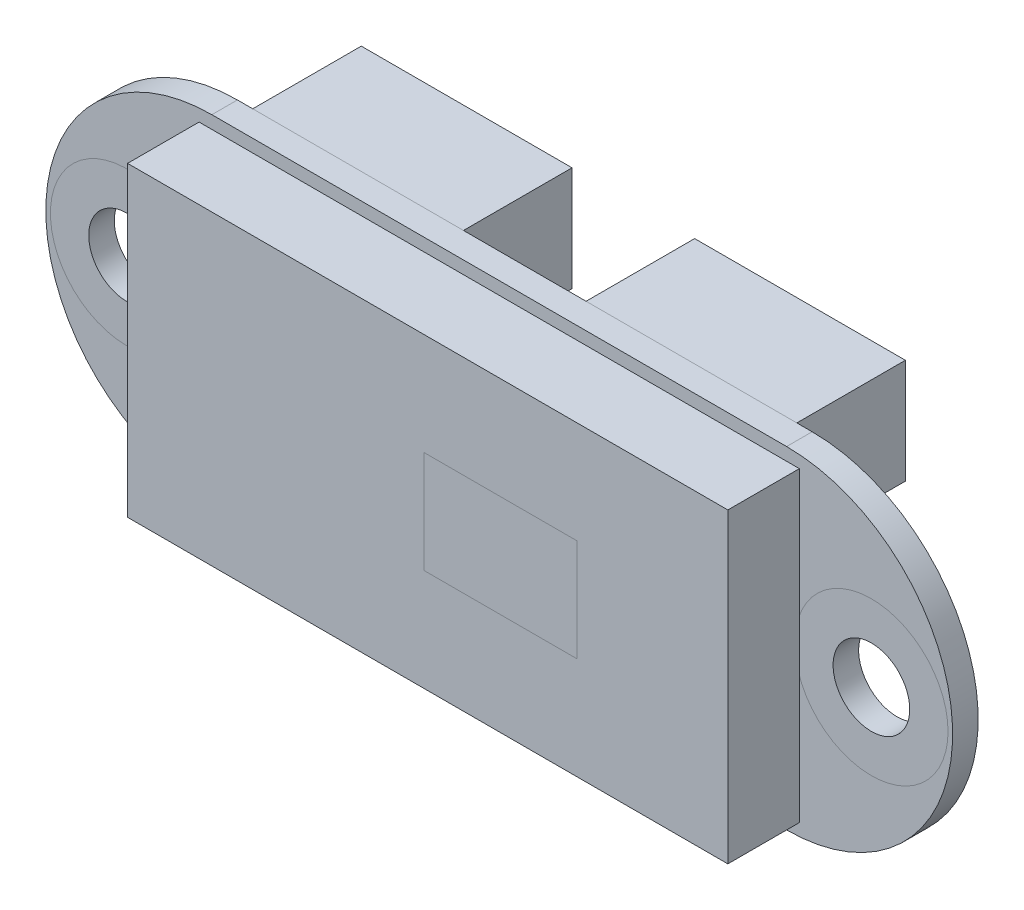
SolidWorks part; units mm, degrees
ref_plane "前视基准面" through (0, 0, 0) normal (0, 0, 1) x (1, 0, 0)
ref_plane "上视基准面" through (0, 0, 0) normal (0, 1, 0) x (1, 0, 0)
ref_plane "右视基准面" through (0, 0, 0) normal (1, 0, 0) x (0, 0, -1)
sketch "草图1" plane through (0, 0, 0) normal (0, 0, 1) x (1, 0, 0)
  line L1 (-49.5108, 21.8667) -> (-27.0108, 21.8667)
  line L3 (-49.5108, 8.8667) -> (-27.0108, 8.8667)
  arc A0 (-49.5108, 21.8667) -> (-49.5108, 8.8667) centre (-49.5108, 15.3667) ccw
  arc A1 (-27.0108, 8.8667) -> (-27.0108, 21.8667) centre (-27.0108, 15.3667) ccw
  circle A2 centre (-52.8308, 15.3667) radius 3
  circle A3 centre (-23.6908, 15.3667) radius 3
  point P10 (-38.2608, 21.8667)
  point P11 (-38.2608, 8.8667)
  dimension "D3" = 14.57
  dimension "D5" = 6
  dimension "D6" = 6
  dimension "D1" = 22.5
  dimension "D2" = 13
  dimension "D4" = 14.57
extrude "凸台-拉伸1" add sketch "草图1" along normal blind 1
sketch "草图2" plane through (0, 0, 1) normal (0, 0, 1) x (1, 0, 0)
  circle A0 centre (-52.8308, 15.3667) radius 1.5
  circle A1 centre (-23.6908, 15.3667) radius 1.5
  circle A2 centre (-23.6908, 15.3667) radius 3
  circle A3 centre (-52.8308, 15.3667) radius 3
extrude "凸台-拉伸2" add sketch "草图2" against normal blind 1 separate body
sketch "草图3" plane through (0, 0, 1) normal (0, 0, 1) x (1, 0, 0)
  line L0 (-27.0108, 21.8667) -> (-49.5108, 21.8667) construction
  line L1 (-50.0108, 21.3667) -> (-26.5108, 21.3667)
  line L2 (-50.0108, 21.3667) -> (-50.0108, 9.3667)
  line L3 (-50.0108, 9.3667) -> (-26.5108, 9.3667)
  line L4 (-26.5108, 21.3667) -> (-26.5108, 9.3667)
  line L6 (-38.4108, 17.3667) -> (-32.4108, 17.3667)
  line L7 (-38.4108, 17.3667) -> (-38.4108, 13.3667)
  line L8 (-38.4108, 13.3667) -> (-32.4108, 13.3667)
  line L9 (-32.4108, 17.3667) -> (-32.4108, 13.3667)
  point P4 (-50.0108, 15.3667)
  point P7 (-38.2608, 21.3667)
  point P8 (-38.2608, 21.8667)
  dimension "D1" = 6.5
  dimension "D2" = 12
  dimension "D3" = 23.5
  dimension "D4" = 0
  dimension "D5" = 4
  dimension "D6" = 6
  dimension "D7" = 5.9
  dimension "D8" = 4
extrude "凸台-拉伸3" add sketch "草图3" along normal blind 2.8 separate body
sketch "草图4" plane through (0, 0, 3.8) normal (0, 0, 1) x (1, 0, 0)
  line L1 (-38.4108, 17.3667) -> (-32.4108, 17.3667)
  line L2 (-38.4108, 17.3667) -> (-38.4108, 13.3667)
  line L3 (-38.4108, 13.3667) -> (-32.4108, 13.3667)
  line L4 (-32.4108, 17.3667) -> (-32.4108, 13.3667)
extrude "凸台-拉伸4" add sketch "草图4" against normal blind 2.8 separate body
sketch "草图5" plane through (0, 0, 0) normal (0, 0, -1) x (-1, 0, 0)
  line L0 (27.0108, 21.8667) -> (49.5108, 21.8667) construction
  line L1 (27.6108, 21.8667) -> (35.8608, 21.8667)
  line L2 (27.6108, 21.8667) -> (27.6108, 17.7667)
  line L3 (27.6108, 17.7667) -> (35.8608, 17.7667)
  line L4 (35.8608, 21.8667) -> (35.8608, 17.7667)
  line L5 (49.5108, 8.8667) -> (27.0108, 8.8667) construction
  line L6 (40.6608, 21.8667) -> (48.9108, 21.8667)
  line L7 (40.6608, 21.8667) -> (40.6608, 17.7667)
  line L8 (40.6608, 17.7667) -> (48.9108, 17.7667)
  line L9 (48.9108, 21.8667) -> (48.9108, 17.7667)
  point P10 (31.7358, 21.8667)
  point P11 (38.2608, 21.8667)
  point P12 (44.7858, 21.8667)
  point P15 (38.2608, 8.8667)
  dimension "D1" = 8.25
  dimension "D2" = 4.1
  dimension "D3" = 4.1
  dimension "D4" = 8.25
  dimension "D5" = 6.525
  dimension "D6" = 6.525
extrude "凸台-拉伸5" add sketch "草图5" along normal blind 4.25 separate body
